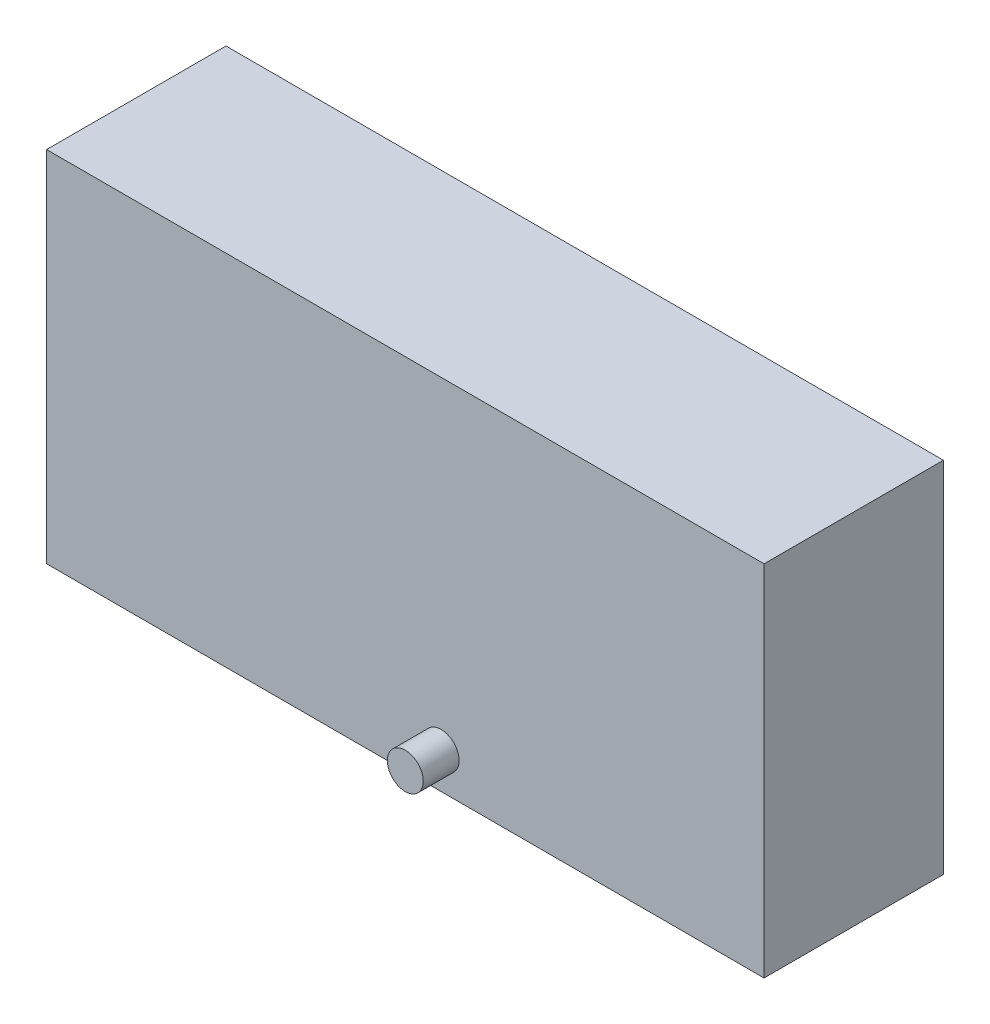
SolidWorks part; units mm, degrees
ref_plane "前视基准面" through (0, 0, 0) normal (0, 0, 1) x (1, 0, 0)
ref_plane "上视基准面" through (0, 0, 0) normal (0, 1, 0) x (1, 0, 0)
ref_plane "右视基准面" through (0, 0, 0) normal (1, 0, 0) x (0, 0, -1)
other "Configuration Table"
sketch "草图1" plane through (0, 0, 0) normal (0, 0, 1) x (1, 0, 0)
  line L1 (0, 0) -> (20, 0)
  line L2 (0, 0) -> (0, 20)
  line L3 (0, 20) -> (20, 20)
  line L4 (20, 0) -> (20, 20)
extrude "BaseBox" add sketch "草图1" along normal blind 10
sketch "草图2" plane through (0, 0, 10) normal (0, 0, 1) x (1, 0, 0)
  circle A0 centre (2, 2) radius 1
extrude "BossSeed" add sketch "草图2" along normal blind 2
mirror "Mirror" about plane through (0, 0, 0) normal (1, 0, 0) of "BaseBox"
